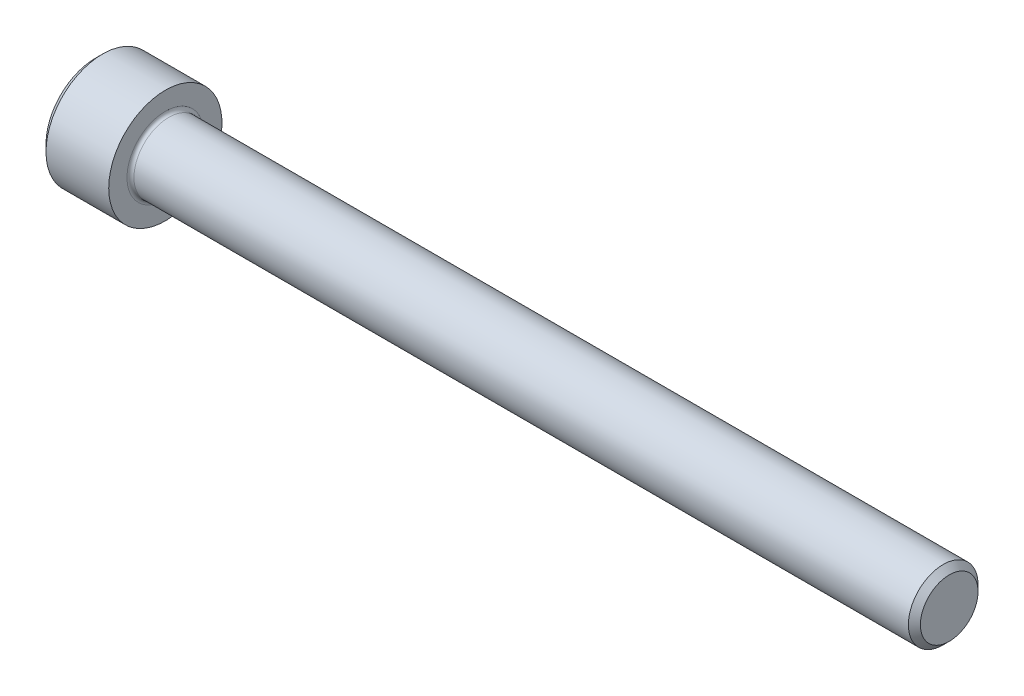
SolidWorks part; units mm, degrees
revolve "Base-Revolve" add sketch "BodySke"
sketch "BodySke" plane through (0, 0, 0) normal (0, 0, 1) x (1, 0, 0)
  line L0 (0, 0) -> (0, 5.7)
  line L1 (0.8, 6.5) -> (8, 6.5)
  line L2 (8, 6.5) -> (8, 4)
  line L3 (8, 4) -> (97.3095, 4)
  line L4 (98, 3.3095) -> (98, 0)
  line L5 (98, 0) -> (0, 0)
  line L6 (-31.75, 0) -> (127, 0) construction
  line L7 (0, 5.7) -> (0.8, 6.5)
  line L8 (98, 3.3095) -> (97.3095, 4)
  line L9 (0, -5.7) -> (0.8, -6.5) construction
  line L10 (98, -3.3095) -> (97.3095, -4) construction
  line L11 (9.25, 2.4825) -> (9.25, -3.8675) construction
  line L12 (70, 2.4825) -> (70, -3.8675) construction
  line L13 (48, 2.4825) -> (48, -3.8675) construction
  dimension "Diameter" = 8
  dimension "Head_ht" = 8
  dimension "Length" = 90
  dimension "Body_ch_ang" = 45
  dimension "Head_dia" = 13
  dimension "Head_ch_ang" = 45
  dimension "Minor_dia" = 6.619
  dimension "Advance" = 1.25
  dimension "Thread_nom" = 28
  dimension "Thread_length" = 50
  dimension "Head_ch_ht" = 0.8
cosmetic thread "ThreadCosmetic" [suppressed]
fillet "Fillet1" radius 0.4 1 edges at (8, 0, 4)
material "Alloy Steel (SS)"
ref_plane "Plane1" through (0, 0, 0) normal (0, 0, 1) x (1, 0, 0)
ref_plane "Plane2" through (0, 0, 0) normal (0, 1, 0) x (1, 0, 0)
ref_plane "Plane3" through (0, 0, 0) normal (1, 0, 0) x (0, 0, -1)
other "Configuration Table"
sketch "Sketch2" plane through (0, 0, 0) normal (0, 0, 1) x (1, 0, 0)
  line L0 (0, 3.0475) -> (4, 3.0475)
  line L1 (4, 3.0475) -> (5.7595, 0)
  line L2 (-31.75, 0) -> (127, 0) construction
  line L3 (5.7595, 0) -> (0, 0)
  line L4 (0, 0) -> (0, 3.0475)
  line L5 (0, 5.7) -> (0, -5.7) construction
  line L6 (0, 0) -> (47.625, 0) construction
  line L7 (8, -6.5) -> (8, 6.5) construction
  dimension "D1" = 3.0475
  dimension "D2" = 60
revolve "Hex-PreBroach" cut sketch "Sketch2" angle 360 about L6
sketch "Sketch3" plane through (0, 0, 0) normal (-1, 0, 0) x (0, 0.5, 0.866)
  line L0 (1.7595, 3.0475) -> (-1.7595, 3.0475)
  line L1 (-1.7595, 3.0475) -> (-3.5189, 0)
  line L2 (1.7595, 3.0475) -> (3.5189, 0)
  line L3 (1.7595, -3.0475) -> (3.5189, 0)
  line L4 (1.7595, -3.0475) -> (-1.7595, -3.0475)
  line L5 (-1.7595, -3.0475) -> (-3.5189, 0)
  dimension "D1" = 3.0475
  dimension "D2" = 3.0475
  dimension "Hex_size" = 6.095
extrude "Hex" cut sketch "Sketch3" against normal blind 4
sketch "Sketch4" plane through (0, 0, 0) normal (-1, 0, 0) x (0, 0, 1)
  line L0 (0, 0) -> (3.7846, 0)
  line L1 (0, 0) -> (6.1484, 3.5498) construction
  line L2 (0, 0) -> (1.8923, 3.2776)
  line L3 (3.1235, 0.8061) -> (3.6229, 1.0945)
  line L4 (2.2599, 2.3019) -> (2.7593, 2.5903)
  arc A0 (3.1235, 0.8061) -> (2.2599, 2.3019) centre (0, 0) ccw
  arc A1 (3.7846, 0) -> (3.6229, 1.0945) centre (0, 0) ccw
  arc A2 (1.8923, 3.2776) -> (2.7593, 2.5903) centre (0, 0) cw
  dimension "D1" = 30
  dimension "D2" = 60
  dimension "Spline_p_dim" = 1.7272
  dimension "D3" = 0.8636
extrude "Spline" [suppressed] cut sketch "Sketch4" against normal blind 4
pattern_circular "CirPattern1" [suppressed] count 6 every 60
sketch "Sketch5" plane through (0, 0, 0) normal (0, 0, 1) x (1, 0, 0)
  line L0 (-31.75, 0) -> (127, 0) construction
  line L2 (0, 5.7) -> (0, -5.7) construction
  circle A0 centre (2.7, 0) radius 0.675
  dimension "Drilled_hole_dia" = 1.35
  dimension "Drilled_hole_loc" = 2.7
extrude "Hole" [suppressed] cut sketch "Sketch5" against normal through all and the other way through all
pattern_circular "Drilled-4" [suppressed] count 2 every 60
pattern_circular "Drilled-6" [suppressed] count 3 every 60
sketch "ThdSchSke" plane through (0, 0, 0) normal (0, 0, 1) x (1, 0, 0)
  line L0 (70, -3.3095) -> (69.5165, -4)
  line L1 (70, -3.3095) -> (70.4835, -4)
  line L2 (70.4835, -4) -> (70.4835, -5)
  line L3 (-3.175, 0) -> (5.1513, 0) construction
  line L5 (70.4835, -5) -> (69.5165, -5)
  line L6 (69.5165, -5) -> (69.5165, -4)
  line L7 (0, 5.7) -> (0, -5.7) construction
  dimension "Thread_minor" = 6.619
  dimension "Diameter" = 8
  dimension "Start" = 70
revolve "ThreadSchematic" [suppressed] cut sketch "ThdSchSke" angle 360 about L3
pattern_linear "ThdSchPat" [suppressed]
equation "\"D2@Sketch3\" = \"Hex_size@Sketch3\" / 2"
equation "\"D1@Sketch3\" = \"Hex_size@Sketch3\" / 2"
equation "\"D1@Sketch2\" = \"Hex_size@Sketch3\" / 2"
equation "\"D3@Sketch4\" = \"Spline_p_dim@Sketch4\" / 2"
equation "\"Thread_minor@ThreadCosmetic\"  =  \"Minor_dia@BodySke\""
equation "\"D2@CirPattern1\" = 360 / \"Num_teeth@CirPattern1\""
equation "\"Wall_thickness@Sketch2\" = \"Head_ht@BodySke\" - \"Key_eng@Hex\""
equation "\"Thread_length@ThreadCosmetic\" = ((sgn( (\"Length@BodySke\" - \"Advance@BodySke\" ) - \"Thread_nom@BodySke\" )-1)*( (\"Length@BodySke\" - \"Advance@BodySke\" ) - \"Thread_nom@BodySke\" ))/-2+ \"Thread_nom@BodySke\""
equation "\"Thread_minor@ThdSchSke\" = \"Minor_dia@BodySke\""
equation "\"Diameter@ThdSchSke\" = \"Diameter@BodySke\""
equation "\"Overcut@ThdSchSke\" = \"Diameter@BodySke\" * 1.25"
equation "\"Start@ThdSchSke\" = \"Head_ht@BodySke\" + \"Length@BodySke\" - \"Thread_length@ThreadCosmetic\"  '---Non-countersunk---"
equation "\"Num_threads@ThdSchPat\" = int( \"Thread_length@ThreadCosmetic\" / \"Advance@BodySke\" + 0.999 )  + 1"
equation "\"Advance@ThdSchPat\" = \"Thread_length@ThreadCosmetic\" /  (\"Num_threads@ThdSchPat\" - 1) 'relax it"
equation "\"Num_threads@ThdSchPat\" = \"Num_threads@ThdSchPat\" - sgn( \"Num_threads@ThdSchPat\" - 1) '---chamfered tips only---"
